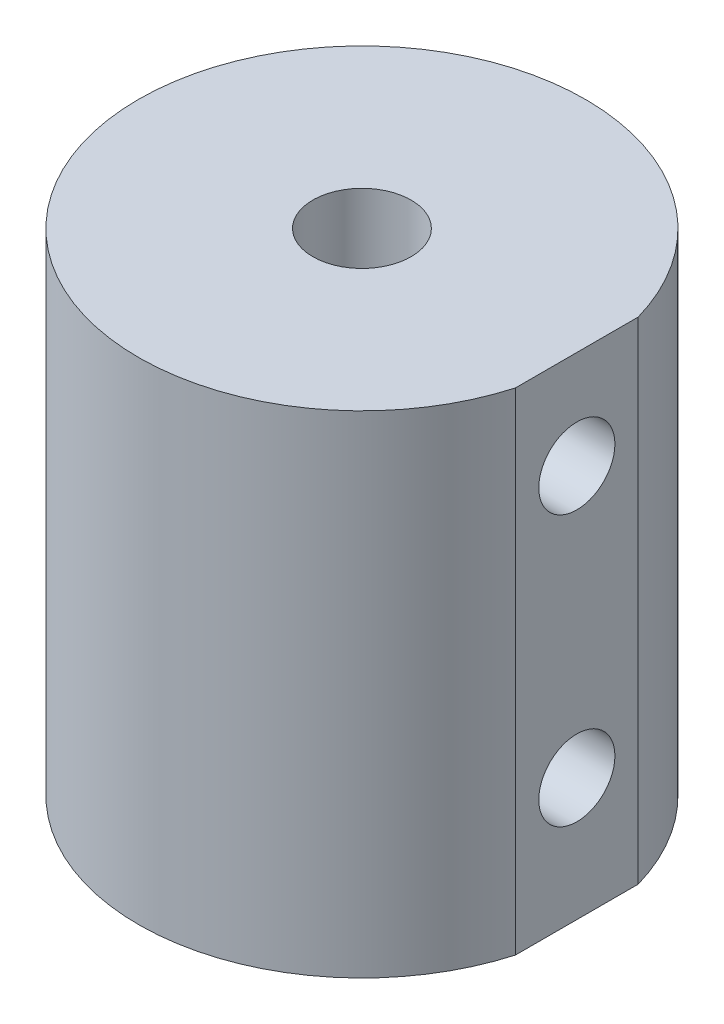
SolidWorks part; units mm, degrees
material "ePA-CF"
ref_plane "Front Plane" through (0, 0, 0) normal (0, 0, 1) x (1, 0, 0)
ref_plane "Top Plane" through (0, 0, 0) normal (0, 1, 0) x (1, 0, 0)
ref_plane "Right Plane" through (0, 0, 0) normal (1, 0, 0) x (0, 0, -1)
sketch "Sketch1" plane through (0, 0, 0) normal (0, 1, 0) x (1, 0, 0)
  line L1 (2, 3.3) -> (-2, 3.3)
  line L2 (2, 3.3) -> (2, 7.3)
  line L3 (2, 7.3) -> (-2, 7.3)
  line L4 (-2, 3.3) -> (-2, 7.3)
  circle A0 centre (0, 0) radius 18.2
  circle A1 centre (0, 0) radius 6.2
  point P8 (0, 3.3)
  dimension "D1" = 12.4
  dimension "D5" = 12
  dimension "D2" = 9.5
  dimension "D3" = 4
  dimension "D4" = 4
extrude "Boss-Extrude1" add sketch "Sketch1" along normal blind 22 contours A0 A1 L4 L3 L2
sketch "Sketch5" plane through (0, 22, 0) normal (0, 1, 0) x (1, 0, 0)
  circle A0 centre (0, 0) radius 4
  circle A1 centre (0, 0) radius 18.2
  circle A2 centre (0, 0) radius 18.2 construction
  dimension "D1" = 8
extrude "Boss-Extrude4" add sketch "Sketch5" along normal blind 18
sketch "Sketch6" plane through (0, 0, 0) normal (0, -1, 0) x (1, 0, 0)
  line L0 (17.4997, 5) -> (17.4997, -5)
  circle A0 centre (0, 0) radius 18.2 construction
  circle M6 centre (0, 0) radius 18.2
  dimension "D1" = 10
extrude "Cut-Extrude1" cut sketch "Sketch6" against normal through all contours L0 M6
sketch "Sketch7" plane through (17.4997, 0, 0) normal (1, 0, 0) x (0, 0, -1)
  line L0 (-5, 0) -> (5, 0) construction
  line L1 (-5, 40) -> (5, 40) construction
  circle A0 centre (0, 10) radius 3.1
  circle A1 centre (0, 32) radius 3.1
  dimension "D1" = 6.2
  dimension "D2" = 6.2
  dimension "D3" = 10
  dimension "D4" = 8
extrude "Cut-Extrude2" cut sketch "Sketch7" against normal blind 18
